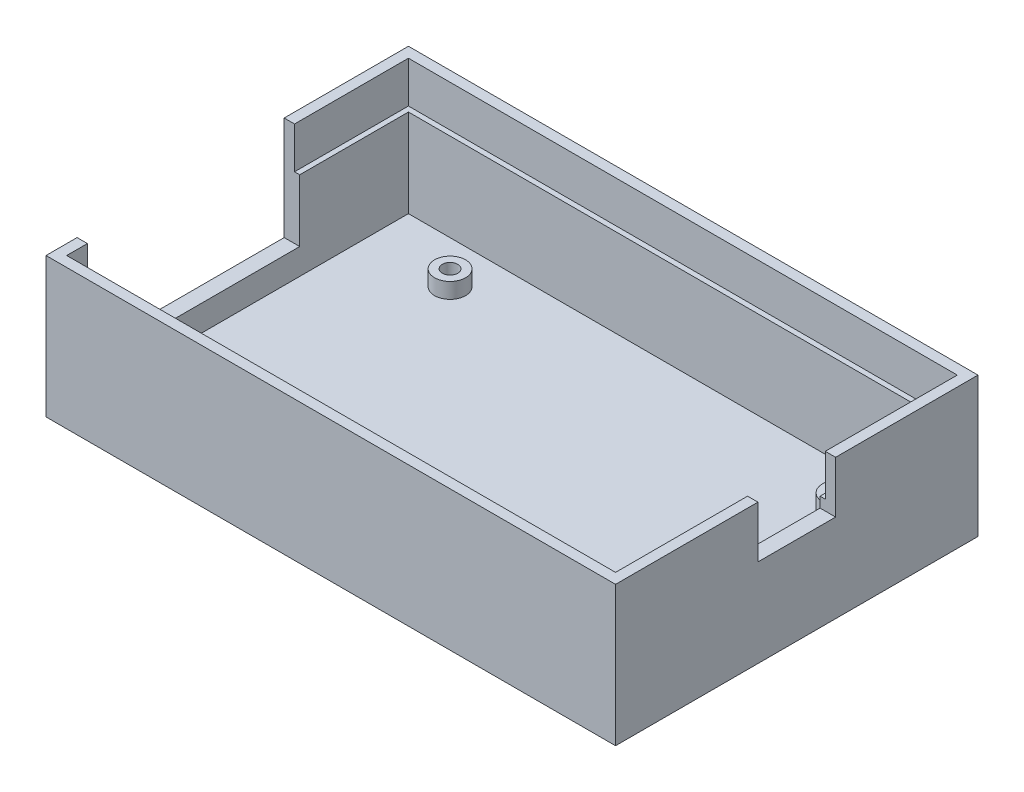
SolidWorks part; units mm, degrees
ref_plane "Alzado" through (0, 0, 0) normal (0, 0, 1) x (1, 0, 0)
ref_plane "Planta" through (0, 0, 0) normal (0, 1, 0) x (1, 0, 0)
ref_plane "Vista lateral" through (0, 0, 0) normal (1, 0, 0) x (0, 0, -1)
sketch "Croquis1" plane through (0, 0, 0) normal (0, 1, 0) x (1, 0, 0)
  line L1 (-55, -35) -> (55, -35)
  line L2 (-55, -35) -> (-55, 35)
  line L3 (-55, 35) -> (55, 35)
  line L4 (55, -35) -> (55, 35)
  line L5 (-55, -35) -> (55, 35) construction
  line L6 (-55, 35) -> (55, -35) construction
  point P0 (0, 0)
  dimension "D1" = 70
  dimension "D2" = 110
extrude "Saliente-Extruir1" add sketch "Croquis1" along normal blind 2
sketch "Croquis2" plane through (0, 2, 0) normal (0, 1, 0) x (1, 0, 0)
  line L1 (-55, -35) -> (55, -35)
  line L2 (-55, -35) -> (-55, 35)
  line L3 (-55, 35) -> (55, 35)
  line L4 (55, -35) -> (55, 35)
  line L5 (-55, -35) -> (55, 35) construction
  line L6 (-55, 35) -> (55, -35) construction
  line L7 (-52, -32) -> (52, -32)
  line L8 (-52, -32) -> (-52, 32)
  line L9 (-52, 32) -> (52, 32)
  line L10 (52, -32) -> (52, 32)
  line L11 (-52, -32) -> (52, 32) construction
  line L12 (-52, 32) -> (52, -32) construction
  point P0 (0, 0)
  point P7 (0, 0)
  dimension "D1" = 3
  dimension "D2" = 3
extrude "Saliente-Extruir2" add sketch "Croquis2" along normal blind 25
sketch "Croquis3" plane through (0, 27, 0) normal (0, 1, 0) x (1, 0, 0)
  line L0 (52, 32) -> (-52, 32) construction
  line L1 (-53, -33) -> (53, -33)
  line L2 (-53, -33) -> (-53, 33)
  line L3 (-53, 33) -> (53, 33)
  line L4 (53, -33) -> (53, 33)
  line L5 (-53, -33) -> (53, 33) construction
  line L6 (-53, 33) -> (53, -33) construction
  line L7 (-52, 32) -> (-52, -32) construction
  point P0 (0, 0)
  dimension "D1" = 1
  dimension "D2" = 1
extrude "Cortar-Extruir1" cut sketch "Croquis3" against normal blind 8
sketch "Croquis4" plane through (0, 2, 0) normal (0, 1, 0) x (1, 0, 0)
  line L0 (-52, -32) -> (-52, 32) construction
  line L1 (-52, 32) -> (-52, -32) construction
  line L3 (52, -32) -> (-52, -32) construction
  line L4 (-52, -32) -> (52, -32) construction
  circle A0 centre (-37.03, -24.46) radius 3
  circle A1 centre (-35.76, 23.8) radius 3
  circle A2 centre (39.17, 23.8) radius 3
  circle A3 centre (45.52, -24.46) radius 3
  dimension "D1" = 6
  dimension "D2" = 6
  dimension "D3" = 6
  dimension "D4" = 6
  dimension "D5" = 14.97
  dimension "D6" = 16.24
  dimension "D7" = 91.17
  dimension "D8" = 97.52
  dimension "D9" = 7.54
  dimension "D10" = 55.8
  dimension "D11" = 55.8
  dimension "D12" = 7.54
extrude "Saliente-Extruir3" add sketch "Croquis4" along normal blind 3
sketch "Croquis6" plane through (0, 5, 0) normal (0, 1, 0) x (1, 0, 0)
  circle A0 centre (-35.76, 23.8) radius 1.5
  circle A1 centre (-37.03, -24.46) radius 1.5
  circle A2 centre (39.17, 23.8) radius 1.5
  circle A3 centre (45.52, -24.46) radius 1.5
  dimension "D1" = 3
  dimension "D2" = 3
  dimension "D3" = 3
  dimension "D4" = 3
extrude "Cortar-Extruir2" cut sketch "Croquis6" against normal blind 4
sketch "Croquis7" plane through (0, 27, 0) normal (0, 1, 0) x (1, 0, 0)
  line L1 (-58, -29) -> (-52, -29)
  line L2 (-58, -29) -> (-58, 11)
  line L3 (-58, 11) -> (-52, 11)
  line L4 (-52, -29) -> (-52, 11)
  line L5 (-58, -29) -> (-52, 11) construction
  line L6 (-58, 11) -> (-52, -29) construction
  line L8 (-55, -35) -> (55, -35) construction
  point P7 (0, 0)
  dimension "D1" = 6
  dimension "D2" = 40
extrude "Cortar-Extruir3" cut sketch "Croquis7" against normal blind 20
sketch "Croquis8" plane through (0, 27, 0) normal (0, 1, 0) x (1, 0, 0)
  line L0 (53, -33) -> (53, 33) construction
  line L1 (48.3231, -7.5) -> (57.6769, -7.5)
  line L2 (48.3231, -7.5) -> (48.3231, 7.5)
  line L3 (48.3231, 7.5) -> (57.6769, 7.5)
  line L4 (57.6769, -7.5) -> (57.6769, 7.5)
  line L5 (48.3231, -7.5) -> (57.6769, 7.5) construction
  line L6 (48.3231, 7.5) -> (57.6769, -7.5) construction
  point P0 (53, 0)
  dimension "D1" = 15
extrude "Cortar-Extruir4" cut sketch "Croquis8" against normal blind 10
equation "\"D6@Croquis4\"=15.24+1"
equation "\"D11@Croquis4\"=\"D10@Croquis4\""
equation "\"D12@Croquis4\"=\"D9@Croquis4\""
equation "\"D1@Croquis7\"=3+3"
